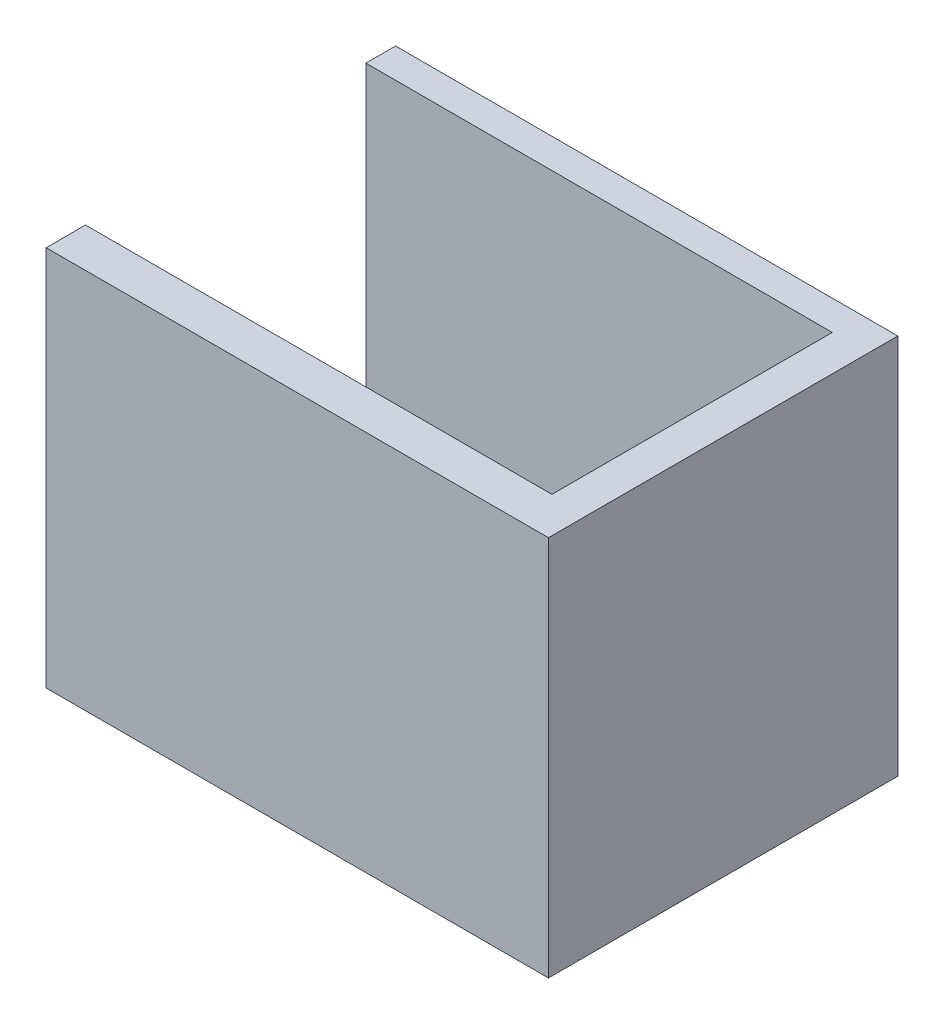
SolidWorks part; units mm, degrees
ref_plane "Front Plane" through (0, 0, 0) normal (0, 0, 1) x (1, 0, 0)
ref_plane "Top Plane" through (0, 0, 0) normal (0, 1, 0) x (1, 0, 0)
ref_plane "Right Plane" through (0, 0, 0) normal (1, 0, 0) x (0, 0, -1)
sketch "Sketch1" plane through (0, 0, 0) normal (0, 1, 0) x (1, 0, 0)
  line L0 (-62.125, 33.674) -> (84.666, 33.674)
  line L1 (-62.125, 43.0202) -> (95.9364, 43.0202)
  line L2 (-62.125, 43.0202) -> (-62.125, 33.674)
  line L3 (-62.125, -66.9356) -> (95.9364, -66.9356)
  line L4 (95.9364, 43.0202) -> (95.9364, -66.9356)
  line L5 (84.666, 33.674) -> (84.666, -54.5656)
  line L6 (84.666, -54.5656) -> (-62.125, -54.5656)
  line L7 (-62.125, -54.5656) -> (-62.125, -66.9356)
extrude "Boss-Extrude1" add sketch "Sketch1" along normal blind 120
sketch "Sketch2" plane through (0, 0, 0) normal (0, -1, 0) x (1, 0, 0)
  line L1 (-62.125, 66.9356) -> (95.9364, 66.9356)
  line L2 (-62.125, 66.9356) -> (-62.125, -43.0202)
  line L3 (-62.125, -43.0202) -> (95.9364, -43.0202)
  line L4 (95.9364, 66.9356) -> (95.9364, -43.0202)
extrude "Boss-Extrude2" add sketch "Sketch2" against normal blind 5
